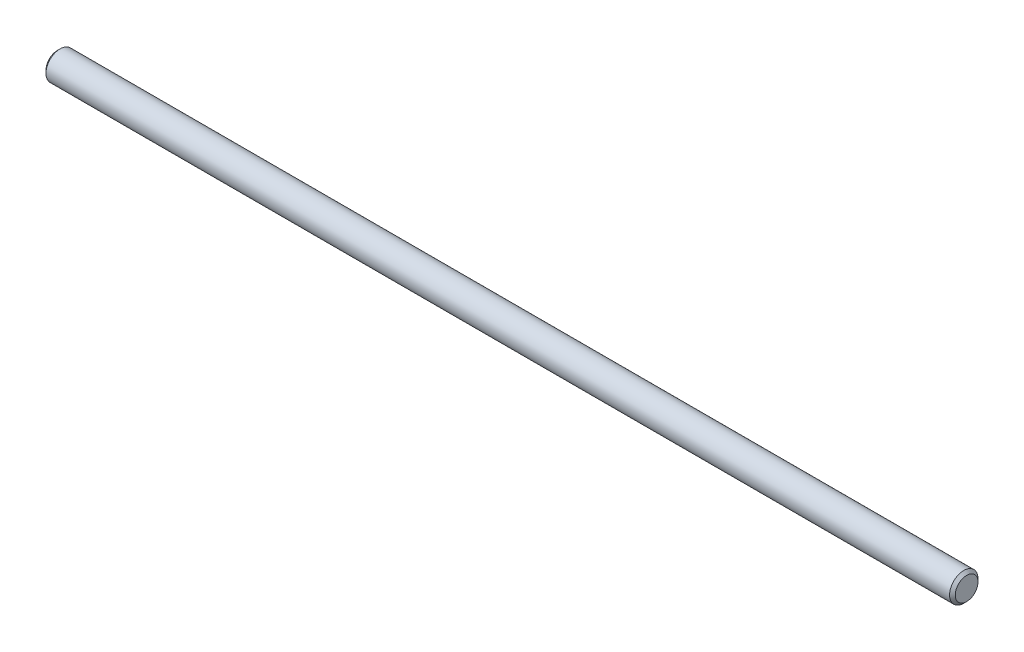
SolidWorks part; units mm, degrees
ref_plane "Front" through (0, 0, 0) normal (0, 0, 1) x (1, 0, 0)
ref_plane "Top" through (0, 0, 0) normal (0, 1, 0) x (1, 0, 0)
ref_plane "Right" through (0, 0, 0) normal (1, 0, 0) x (0, 0, -1)
sketch "Sketch1" plane through (0, 0, 0) normal (0, 0, 1) x (1, 0, 0)
  line L0 (-25.4, 0) -> (25.4, 0) construction
  line L1 (25.4, 0.7937) -> (25.4, -0.7937) construction
  line L2 (-25.4, 0.7937) -> (-25.4, -0.7937) construction
  dimension "Length" = 50.8
  dimension "Diameter" = 1.5875
sketch "Sketch2" plane through (0, 0, 0) normal (1, 0, 0) x (0, 0, -1)
  circle A0 centre (0, 0) radius 0.7937
extrude "Extrude1" add sketch "Sketch2" against normal up to vertex (25.4 mm away) and the other way up to vertex (25.4 mm away) up to point (-25.4, 0.7937, 0) other way up to point (25.4, 0.7937, 0)
chamfer "Chamfer1" distance 0.1588 angle 45 2 edges at (25.4, 0, -0.7937) (-25.4, 0, -0.7937)
equation "\"D1@Chamfer1\" = \"Diameter@Sketch1\"*.1"
